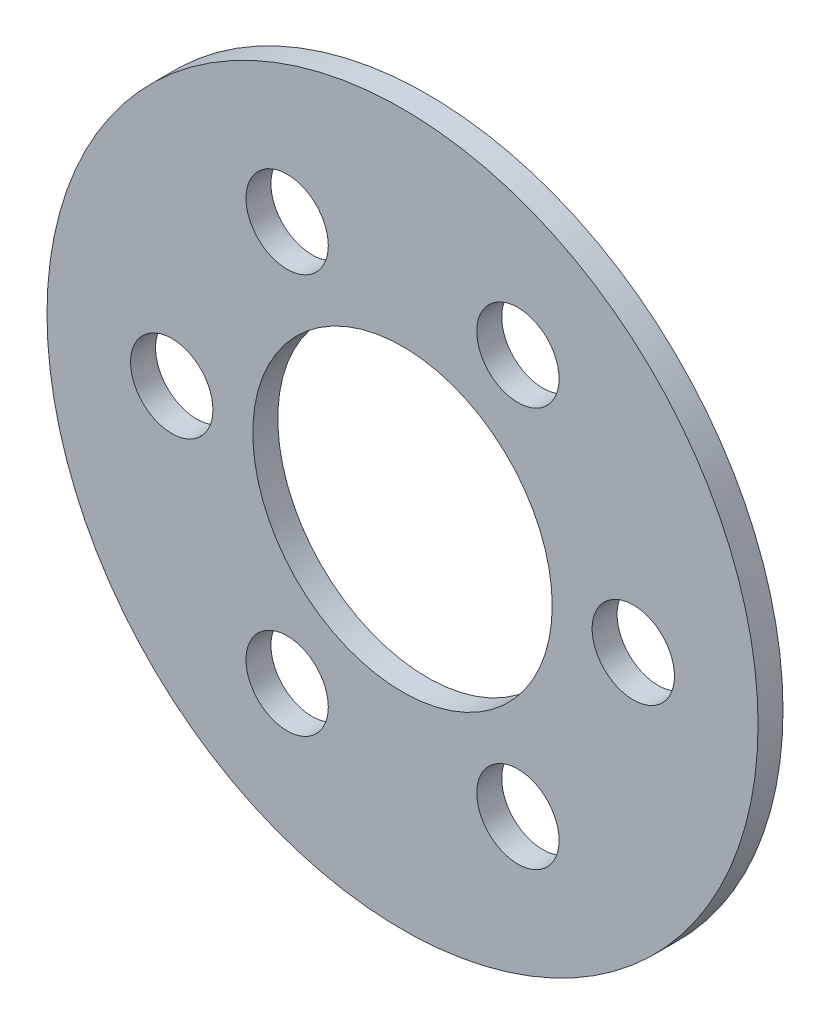
SolidWorks part; units mm, degrees
ref_plane "Ebene vorne" through (0, 0, 0) normal (0, 0, 1) x (1, 0, 0)
ref_plane "Ebene oben" through (0, 0, 0) normal (0, 1, 0) x (1, 0, 0)
ref_plane "Ebene rechts" through (0, 0, 0) normal (1, 0, 0) x (0, 0, -1)
sketch "Skizze1" plane through (0, 0, 0) normal (0, 0, 1) x (1, 0, 0)
  line L0 (-6, 0) -> (-12.5, 0) construction
  circle A0 centre (0, 0) radius 6
  circle A1 centre (0, 0) radius 14.25
  circle A2 centre (0, 0) radius 12.5
  circle A3 centre (-9.25, 0) radius 1.65
  circle A4 centre (-4.625, 8.0107) radius 1.65
  circle A5 centre (4.625, 8.0107) radius 1.65
  circle A6 centre (9.25, 0) radius 1.65
  circle A7 centre (4.625, -8.0107) radius 1.65
  circle A8 centre (-4.625, -8.0107) radius 1.65
  point P9 (0, 0)
  point P21 (0, 0)
  dimension "D1" = 28.5
  dimension "D2" = 25
  dimension "D3" = 6
extrude "Aufsatz-Linear austragen1" add sketch "Skizze1" along normal blind 1
